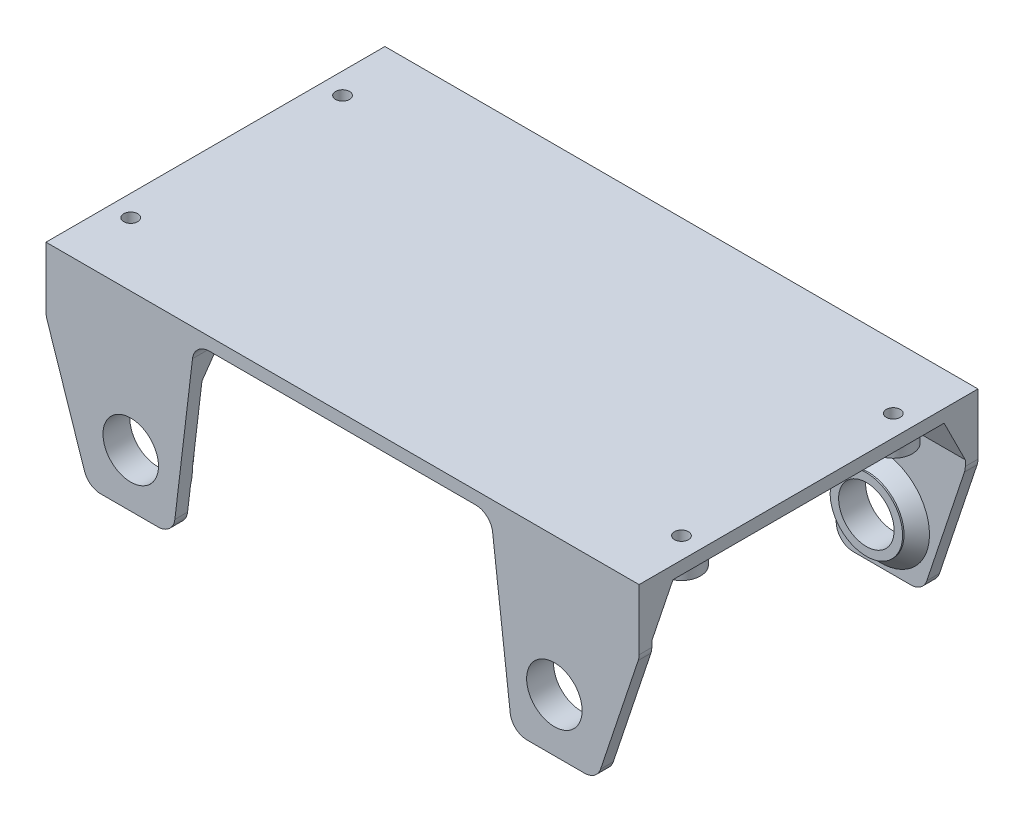
SolidWorks part; units mm, degrees
ref_plane "Alzado" through (0, 0, 0) normal (0, 0, 1) x (1, 0, 0)
ref_plane "Planta" through (0, 0, 0) normal (0, 1, 0) x (1, 0, 0)
ref_plane "Vista lateral" through (0, 0, 0) normal (1, 0, 0) x (0, 0, -1)
sketch "Croquis1" plane through (0, 0, 0) normal (0, 0, 1) x (1, 0, 0)
  line L1 (-70, 22.5) -> (70, 22.5)
  line L2 (-70, 22.5) -> (-70, -22.5)
  line L3 (-70, -22.5) -> (70, -22.5)
  line L4 (70, 22.5) -> (70, -22.5)
  line L5 (-70, 22.5) -> (70, -22.5) construction
  line L6 (-70, -22.5) -> (70, 22.5) construction
  point P0 (0, 0)
  dimension "D1" = 140
  dimension "D2" = 45
extrude "Saliente-Extruir1" add sketch "Croquis1" along normal mid plane 80
sketch "Croquis2" plane through (0, 0, 0) normal (1, 0, 0) x (0, 0, -1)
  line L0 (-37, 19.5) -> (37, 19.5)
  line L2 (-37, 19.5) -> (-37, -22.5)
  line L3 (-40, -22.5) -> (40, -22.5) construction
  line L4 (37, 19.5) -> (37, -22.5)
  line L6 (37, -22.5) -> (-37, -22.5)
  line L7 (-40, 22.5) -> (40, 22.5) construction
  line L8 (-40, -22.5) -> (-40, 22.5) construction
  point P2 (0, 19.5)
  dimension "D1" = 3
  dimension "D2" = 3
extrude "Cortar-Extruir1" cut sketch "Croquis2" against normal through all both and the other way through all
sketch "Croquis3" plane through (0, 0, 40) normal (0, 0, 1) x (1, 0, 0)
  line L0 (-50, -10) -> (50, -10) construction
  circle A0 centre (50, -10) radius 6.55
  circle A1 centre (-50, -10) radius 6.55
  point P2 (0, -10)
  dimension "D1" = 13.1
  dimension "D2" = 100
  dimension "D3" = 10
extrude "Cortar-Extruir2" cut sketch "Croquis3" against normal blind 80
sketch "Croquis10" plane through (0, 0, 37) normal (0, 0, -1) x (-1, 0, 0)
  circle A0 centre (-50, -10) radius 8.55
  circle A1 centre (-50, -10) radius 6.55 construction
  circle A2 centre (-50, -10) radius 6.55
  circle A3 centre (-50, -10) radius 6.55 construction
  circle A4 centre (50, -10) radius 6.55
  circle A5 centre (50, -10) radius 8.55
  circle A6 centre (50, -10) radius 6.55 construction
  dimension "D1" = 2
  dimension "D2" = 2
extrude "Saliente-Extruir3" add sketch "Croquis10" along normal blind 3.35
mirror "Simetría1" about plane through (0, 0, 0) normal (0, 0, 1) of "Saliente-Extruir3"
sketch "Croquis4" plane through (0, 19.5, 0) normal (0, -1, 0) x (1, 0, 0)
  line L0 (-65, 25) -> (-65, -25) construction
  circle A0 centre (-65, 25) radius 1.651
  circle A1 centre (-65, -25) radius 1.651
  point P6 (-65, 0)
  dimension "D1" = 3.302
  dimension "D2" = 50
  dimension "D3" = 65
extrude "Cortar-Extruir3" cut sketch "Croquis4" against normal up to next
sketch "Croquis5" plane through (0, 19.5, 0) normal (0, -1, 0) x (1, 0, 0)
  circle A0 centre (-65, 25) radius 3.5
  circle A1 centre (-65, 25) radius 4.5
  circle A2 centre (-65, -25) radius 3.5
  circle A3 centre (-65, -25) radius 1.651
  circle A4 centre (-65, -25) radius 4.5
  circle A5 centre (-65, 25) radius 1.651
  circle A6 centre (-65, 25) radius 1.651 construction
  circle A8 centre (-65, -25) radius 1.651 construction
  dimension "D1" = 7
  dimension "D2" = 1
  dimension "D3" = 1
extrude "Saliente-Extruir2" add sketch "Croquis5" along normal blind 3 contours A1 A0 | A4 A2
mirror "Simetría2" about plane through (0, 0, 0) normal (1, 0, 0) of "Cortar-Extruir3", "Saliente-Extruir2"
chamfer "Chaflán3" distance 3 angle 45 4 edges at (50, -1.45, -37) (-50, -1.45, -37) (-50, -18.55, 37) (50, -18.55, 37)
sketch "Croquis9" plane through (0, 0, 0) normal (0, 0, 1) x (1, 0, 0)
  line L0 (-40, -22.5) -> (-35, 19.5)
  line L1 (-70, -22.5) -> (70, -22.5) construction
  line L2 (-35, 19.5) -> (35, 19.5)
  line L3 (35, 19.5) -> (40, -22.5)
  line L4 (-40, -22.5) -> (40, -22.5)
  line L5 (70, 22.5) -> (-70, 22.5) construction
  line L6 (-70, 7.5) -> (-60, -22.5)
  line L7 (-70, 22.5) -> (-70, -22.5) construction
  line L8 (-60, -22.5) -> (-70, -22.5)
  line L9 (-70, -22.5) -> (-70, 7.5)
  line L10 (70, 7.5) -> (60, -22.5)
  line L11 (70, -22.5) -> (70, 22.5) construction
  line L12 (60, -22.5) -> (70, -22.5)
  line L13 (70, -22.5) -> (70, 7.5)
  point P4 (0, 19.5)
  dimension "D1" = 70
  dimension "D2" = 80
  dimension "D3" = 3
  dimension "D4" = 10
  dimension "D5" = 30
  dimension "D6" = 30
  dimension "D7" = 10
extrude "Cortar-Extruir5" cut sketch "Croquis9" against normal through all both and the other way through all
fillet "Redondeo1" radius 4 16 edges at (-40, -22.5, 38.5) (-60, -22.5, 38.5) (-70, 7.5, 38.5) (40, -22.5, 38.5) (60, -22.5, 38.5) (70, 7.5, 38.5) (70, 7.5, -38.5) (60, -22.5, -38.5) (40, -22.5, -38.5) (-40, -22.5, -38.5) (-60, -22.5, -38.5) (-70, 7.5, -38.5) (-35, 19.5, -38.5) (35, 19.5, -38.5) (-35, 19.5, 38.5) (35, 19.5, 38.5)
chamfer "Chaflán1" distance 10 distance2 5 4 edges at (50.724, 19.5, -37) (-50.724, 19.5, -37) (-34.1039, 18.4909, -37) (34.1039, 18.4909, -37)
chamfer "Chaflán2" distance 5 distance2 10 4 edges at (50.724, 19.5, 37) (-50.724, 19.5, 37) (-34.1039, 18.4909, 37) (34.1039, 18.4909, 37)
sketch "Croquis12" plane through (0, 19.5, 0) normal (0, -1, 0) x (1, 0, 0)
  line L0 (4.2906, -6.2498) -> (7.2906, -6.2498)
  line L1 (4.2906, 11.2498) -> (7.2906, 11.2498)
  line L2 (4.2906, 11.2498) -> (4.2906, 6.2498)
  line L3 (4.2906, 6.2498) -> (7.2906, 6.2498)
  line L4 (7.2906, 11.2498) -> (7.2906, 6.2498)
  line L5 (4.2906, 11.2498) -> (7.2906, 6.2498) construction
  line L6 (4.2906, 6.2498) -> (7.2906, 11.2498) construction
  line L7 (4.2906, -6.2498) -> (4.2906, -11.2498)
  line L8 (4.2906, -11.2498) -> (7.2906, -11.2498)
  line L9 (7.2906, -6.2498) -> (7.2906, -11.2498)
  line L10 (4.2906, -6.2498) -> (7.2906, -11.2498) construction
  line L11 (4.2906, -11.2498) -> (7.2906, -6.2498) construction
  line L12 (5.7906, 8.7498) -> (5.7906, -8.7498) construction
  point P0 (5.7906, 8.7498)
  point P5 (5.7906, -8.7498)
  point P10 (5.7906, 0)
  dimension "D1" = 5
  dimension "D2" = 3
  dimension "D3" = 5
  dimension "D4" = 3
